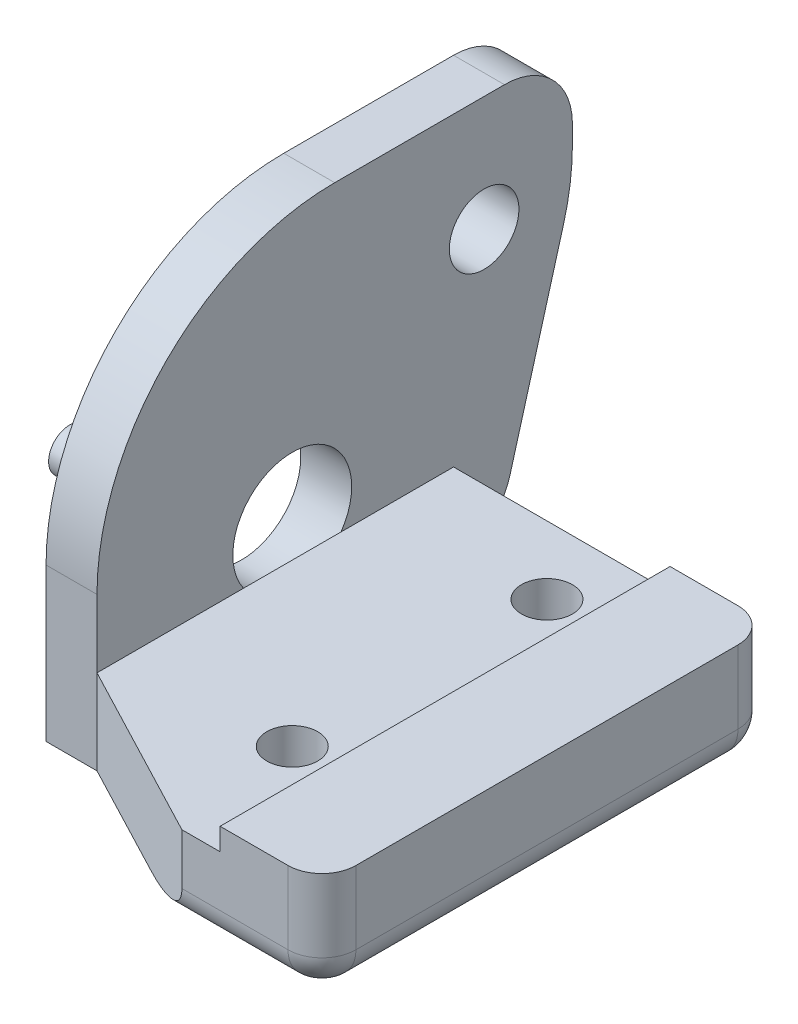
SolidWorks part; units mm, degrees
ref_plane "前视基准面" through (0, 0, 0) normal (0, 0, 1) x (1, 0, 0)
ref_plane "上视基准面" through (0, 0, 0) normal (0, 1, 0) x (1, 0, 0)
ref_plane "右视基准面" through (0, 0, 0) normal (1, 0, 0) x (0, 0, -1)
other "Configuration Table"
sketch "草图1" plane through (0, 0, 0) normal (0, 1, 0) x (1, 0, 0)
  line L0 (0, 0) -> (0, 26.5)
  line L1 (0, 26.5) -> (-18.75, 26.5)
  line L2 (-18.75, 26.5) -> (-18.75, 5.5)
  line L3 (0, 0) -> (-8.25, 0)
  line L4 (-8.25, 0) -> (-18.75, 5.5)
  dimension "D1" = 8.25
  dimension "D2" = 26.5
  dimension "D3" = 18.75
  dimension "D4" = 21
extrude "凸台-拉伸1" add sketch "草图1" against normal blind 5
sketch "草图2" plane through (-18.75, 0, 0) normal (-1, 0, 0) x (0, 0, 1)
  line L0 (-5.5, -5) -> (-33.5, -5)
  line L1 (-33.5, -5) -> (-33.5, 18)
  line L2 (-33.5, 18) -> (-5.5, 18)
  line L3 (-5.5, 18) -> (-5.5, -5)
extrude "凸台-拉伸2" add sketch "草图2" along normal blind 3
sketch "草图3" plane through (0, 0, 0) normal (0, 1, 0) x (1, 0, 0)
  line L0 (0, 0) -> (0, 26.5) construction
  line L2 (0, 26.5) -> (-18.75, 26.5) construction
  line L5 (-9.5, 26.5) -> (-9.5, 0.6548) construction
  line L6 (-18.75, 5.5) -> (-8.25, 0) construction
  circle A0 centre (-9.25, 22.5) radius 1.5
  circle A1 centre (-9.25, 7.5) radius 1.5
  dimension "D1" = 15
  dimension "D2" = 9.25
  dimension "D3" = 4
extrude "切除-拉伸1" cut sketch "草图3" against normal through all contours A0 | A1
sketch "草图4" plane through (-18.75, 0, 0) normal (1, 0, 0) x (0, 0, -1)
  line L0 (0, -5) -> (26.5, -5) construction
  line L2 (26.5, -5) -> (26.5, 0) construction
  circle A0 centre (17, 2) radius 3.5
  circle A1 centre (9.9, 6.2) radius 1.25
  dimension "D3" = 9.5
  dimension "D5" = 2.5
  dimension "D2" = 7
  dimension "D4" = 7.1
extrude "切除-拉伸2" cut sketch "草图4" against normal through all
fillet "圆角2" radius 14 1 edges at (-20.25, 18, -5.5)
fillet "圆角3" radius 2 1 edges at (-9.375, -5, -26.5)
sketch "草图5" plane through (-18.75, 0, 0) normal (1, 0, 0) x (0, 0, -1)
  line L10 (32.9771, 9.1408) -> (29.8204, -2.083)
  line L11 (33.5, 12.9313) -> (33.5, -5)
  line L12 (33.5, -5) -> (24.5, -5) construction
  line L13 (33.5, 18) -> (33.5, -5) construction
  line L14 (33.5, -5) -> (25.9698, -5)
  arc A0 (32.9771, 9.1408) -> (33.5, 12.9313) centre (19.5, 12.9313) ccw
  arc A3 (29.8204, -2.083) -> (25.9698, -5) centre (25.9698, -1) cw
  dimension "D1" = 14
  dimension "D2" = 4
sketch "草图6" plane through (0, 0, 0) normal (0, 1, 0) x (1, 0, 0)
  line L0 (0, 26.5) -> (-6, 26.5)
  line L1 (0, 26.5) -> (-18.75, 26.5) construction
  line L2 (-6, 26.5) -> (-6, 0)
  line L3 (-8.25, 0) -> (0, 0) construction
  line L4 (-6, 0) -> (0, 0)
  line L5 (0, 0) -> (0, 26.5)
extrude "凸台-拉伸3" add sketch "草图6" along normal blind 1.3
fillet "圆角4" radius 2 1 edges at (0, -1.85, 0)
fillet "圆角5" radius 2 5 edges at (-5.125, -5, 0) (0, -0.85, -26.5) (0, -4.4142, -25.9142) (0, -5, -13.25) (-0.5858, -5, -0.5858)
sketch "草图7" plane through (-18.75, 0, 0) normal (1, 0, 0) x (0, 0, -1)
  circle A0 centre (9.9, 6.2) radius 1.25
extrude "凸台-拉伸5" add sketch "草图7" against normal blind 6
sketch "草图9" plane through (-18.75, 0, 0) normal (1, 0, 0) x (0, 0, -1)
  line L1 (28.3, 21.2) -> (33.5, 21.2)
  line L2 (33.5, 21.2) -> (33.5, 18)
  line L3 (33.5, 18) -> (22.5, 18)
  line L4 (19.5, 18) -> (33.5, 18) construction
  line L5 (22.5, 18) -> (22.5, 21.2)
  line L6 (22.5, 21.2) -> (28.3, 21.2)
extrude "凸台-拉伸6" add sketch "草图9" against normal blind 3
sketch "草图11" plane through (-18.75, 0, 0) normal (1, 0, 0) x (0, 0, -1)
  circle A7 centre (28.3, 11.2288) radius 2.05
  point P3 (28.3, 18.2288)
extrude "切除-拉伸3" cut sketch "草图11" against normal blind 3
extrude "切除-拉伸4" cut sketch "草图5" against normal blind 3 contours L10 A3 L14 L11 A0
fillet "圆角6" radius 2 1 edges at (-20.25, 21.2, -22.5)
fillet "圆角7" radius 2 1 edges at (-20.25, 21.2, -33.5)
fillet "圆角8" radius 1 1 edges at (-20.25, 18, -22.5)
sketch "草图12" plane through (-18.75, 0, 0) normal (1, 0, 0) x (0, 0, -1)
  line L0 (21.5, 18) -> (33.5, 18)
  line L1 (33.5, 19.2) -> (33.5, 12.9313) construction
  line L2 (33.5, 18) -> (35.1803, 22.1655)
  line L3 (35.1803, 22.1655) -> (18.8324, 21.8304)
  line L4 (18.8324, 21.8304) -> (21.5, 18)
extrude "切除-拉伸5" cut sketch "草图12" against normal blind 10
fillet "圆角9" radius 4 1 edges at (-20.25, 18, -33.5)
